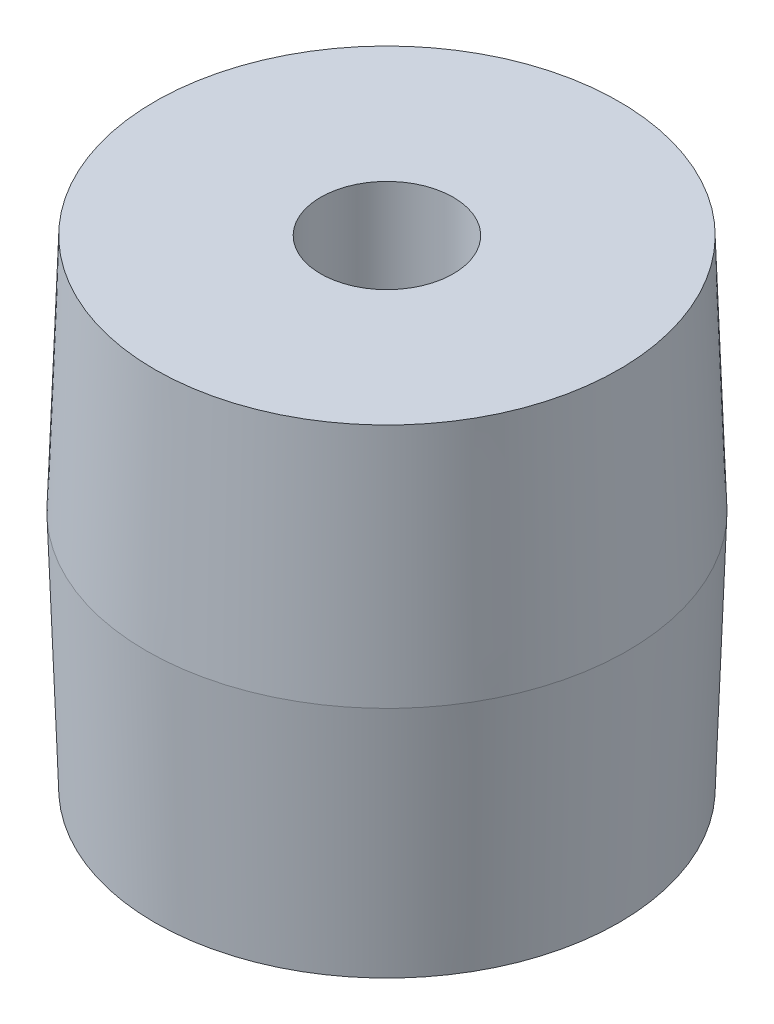
SolidWorks part; units mm, degrees
ref_plane "Front Plane" through (0, 0, 0) normal (0, 0, 1) x (1, 0, 0)
ref_plane "Top Plane" through (0, 0, 0) normal (0, 1, 0) x (1, 0, 0)
ref_plane "Right Plane" through (0, 0, 0) normal (1, 0, 0) x (0, 0, -1)
sketch "Sketch1" plane through (0, 0, 0) normal (0, 1, 0) x (1, 0, 0)
  circle A0 centre (0, 0) radius 9.2075
  dimension "D1" = 18.415
extrude "Boss-Extrude1" add sketch "Sketch1" along normal blind 9.1694 draft 2
mirror "Mirror1" about plane through (0, 0, 0) normal (0, 1, 0) of "Boss-Extrude1"
sketch "Sketch2" plane through (0, -9.1694, 0) normal (0, -1, 0) x (-1, 0, 0)
  circle A0 centre (0, 0) radius 2.54
  dimension "D1" = 5.08
extrude "Cut-Extrude1" cut sketch "Sketch2" against normal through all
